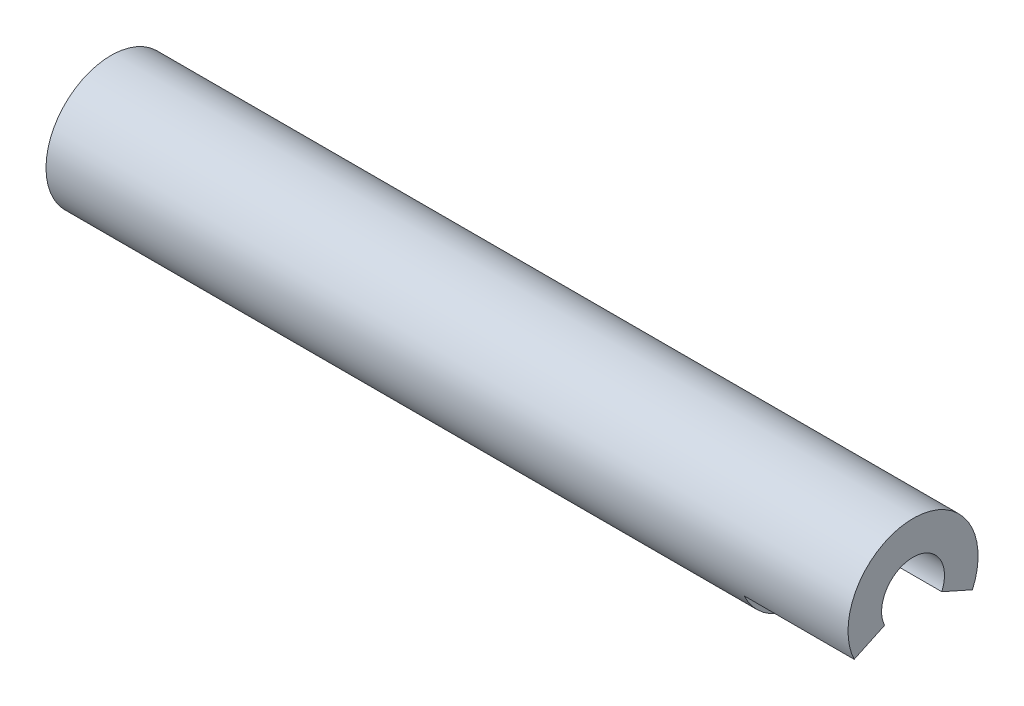
SolidWorks part; units mm, degrees
ref_plane "Ön Düzlem" through (0, 0, 0) normal (0, 0, 1) x (1, 0, 0)
ref_plane "Üst Düzlem" through (0, 0, 0) normal (0, 1, 0) x (1, 0, 0)
ref_plane "Sağ Düzlem" through (0, 0, 0) normal (1, 0, 0) x (0, 0, -1)
ref_plane "Düzlem1" through (0, 0, 0) normal (0, 0, -1) x (-1, 0, 0)
sketch "Çizim1" plane through (0, 0, 0) normal (0, 0, -1) x (-1, 0, 0)
  line L0 (-153, 12.4054) -> (-153, 0)
  line L1 (-153, 0) -> (0, 0)
  line L2 (0, 0) -> (0, 12.4054)
  line L3 (0, 12.4054) -> (-153, 12.4054)
  line L4 (-153, 0) -> (0, 0) construction
  dimension "D1" = 153
revolve "Döndür1" add sketch "Çizim1" angle 360 about L4
sketch "Çizim2" plane through (153, 0, 0) normal (1, 0, 0) x (0, 0, -1)
  line L1 (5.4785, -2.4467) -> (11.3272, -5.0586)
  line L2 (-5.4326, -2.5469) -> (-11.2323, -5.2659)
  arc A0 (5.4785, -2.4467) -> (-5.4326, -2.5469) centre (0, 0) ccw
  circle A1 centre (0, 0) radius 12.4054 construction
  arc A2 (11.3272, -5.0586) -> (-11.2323, -5.2659) centre (0, 0) cw
extrude "Kes-Ekstrüzyon1" cut sketch "Çizim2" against normal blind 21
sketch "Çizim3" plane through (0, 0, 0) normal (-1, 0, 0) x (0, 0, 1)
  arc A0 (2.25, -5.5621) -> (-2.25, -5.5621) centre (0, 0) ccw
  arc A1 (-2.25, -5.5621) -> (2.25, -5.5621) centre (0, 0) ccw
  dimension "D1" = 6
extrude "Kes-Ekstrüzyon2" cut sketch "Çizim3" against normal blind 21
